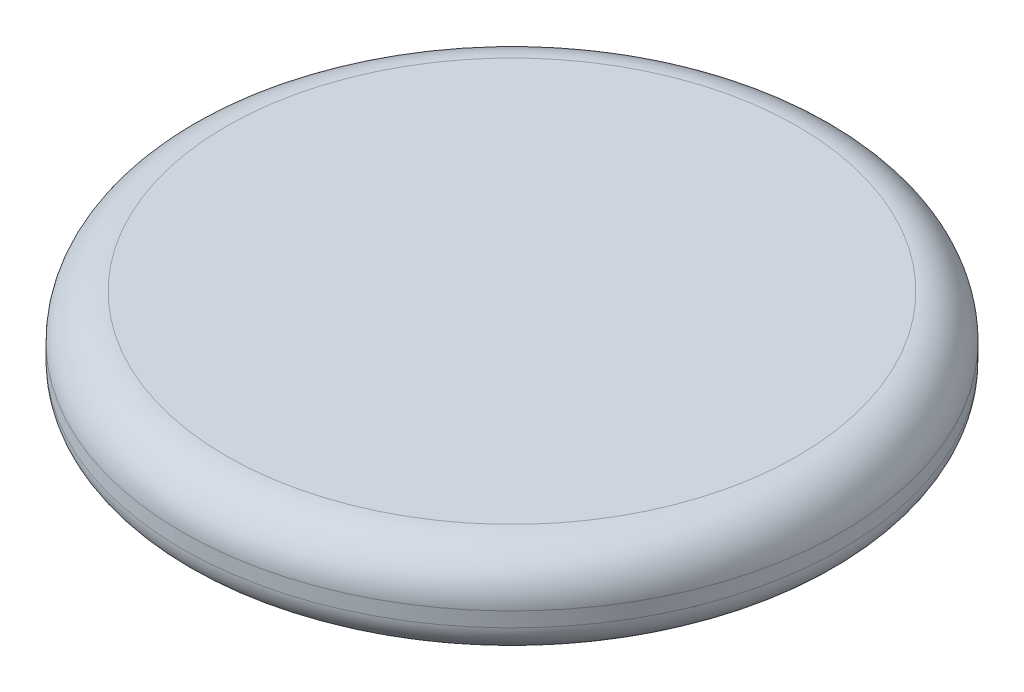
SolidWorks part; units mm, degrees
ref_plane "Front Plane" through (0, 0, 0) normal (0, 0, 1) x (1, 0, 0)
ref_plane "Top Plane" through (0, 0, 0) normal (0, 1, 0) x (1, 0, 0)
ref_plane "Right Plane" through (0, 0, 0) normal (1, 0, 0) x (0, 0, -1)
sketch "Sketch2" plane through (0, 0, 0) normal (0, 1, 0) x (1, 0, 0)
  circle A0 centre (0, 0) radius 57.15
  dimension "D1" = 114.3
extrude "Boss-Extrude1" add sketch "Sketch2" along normal blind 15.24
fillet "Fillet1" radius 7.62 1 edges at (0, 15.24, 57.15)
fillet "Fillet2" radius 5.08 1 edges at (0, 0, 57.15)
sketch "Sketch3" plane through (0, 0, 0) normal (0, -1, 0) x (-1, 0, 0)
  line L0 (0, -52.07) -> (0, 52.07) construction
  line L1 (52.07, 0) -> (-52.07, 0) construction
  circle A0 centre (0, 0) radius 52.07 construction
